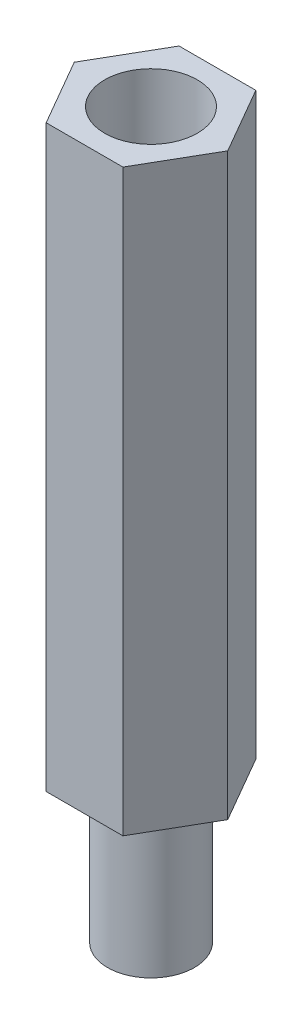
SolidWorks part; units mm, degrees
ref_plane "Front Plane" through (0, 0, 0) normal (0, 0, 1) x (1, 0, 0)
ref_plane "Top Plane" through (0, 0, 0) normal (0, 1, 0) x (1, 0, 0)
ref_plane "Right Plane" through (0, 0, 0) normal (1, 0, 0) x (0, 0, -1)
sketch "Sketch1" plane through (0, 0, 0) normal (0, 1, 0) x (1, 0, 0)
  line L1 (2.65, 0) -> (1.325, 2.295)
  line L2 (1.325, 2.295) -> (-1.325, 2.295)
  line L3 (-1.325, 2.295) -> (-2.65, 0)
  line L4 (-2.65, 0) -> (-1.325, -2.295)
  line L5 (-1.325, -2.295) -> (1.325, -2.295)
  line L6 (1.325, -2.295) -> (2.65, 0)
  circle A0 centre (0, 0) radius 2.295 construction
  dimension "D1" = 5.3
extrude "Boss-Extrude1" add sketch "Sketch1" along normal blind 20
sketch "Sketch2" plane through (0, 20, 0) normal (0, 1, 0) x (1, 0, 0)
  circle A0 centre (0, 0) radius 1.6
  dimension "D1" = 3.2
extrude "Cut-Extrude1" cut sketch "Sketch2" against normal blind 5
sketch "Sketch3" plane through (0, 0, 0) normal (0, -1, 0) x (1, 0, 0)
  circle A0 centre (0, 0) radius 1.5
  dimension "D1" = 3
extrude "Boss-Extrude2" add sketch "Sketch3" along normal blind 5
